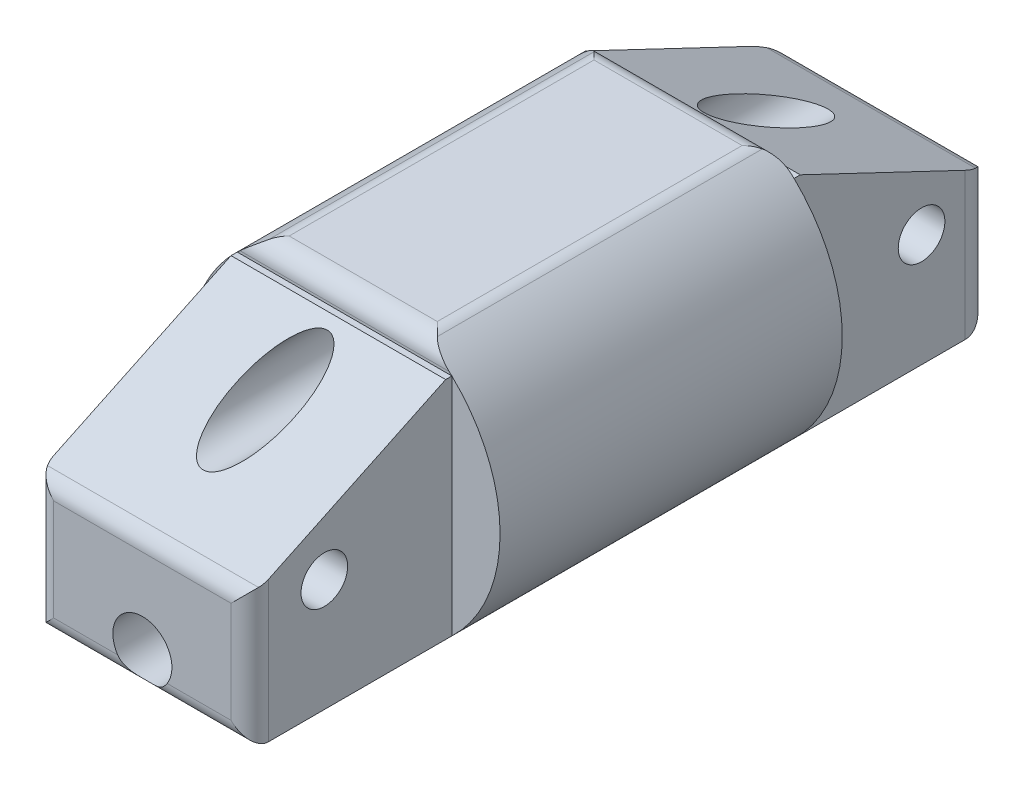
SolidWorks part; units mm, degrees
ref_plane "Front Plane" through (0, 0, 0) normal (0, 0, 1) x (1, 0, 0)
ref_plane "Top Plane" through (0, 0, 0) normal (0, 1, 0) x (1, 0, 0)
ref_plane "Right Plane" through (0, 0, 0) normal (1, 0, 0) x (0, 0, -1)
sketch "Sketch1" plane through (0, 0, 0) normal (0, 0, 1) x (1, 0, 0)
  line L0 (0, 12.7) -> (0, -12.7) construction
  line L1 (-12.7, 0) -> (12.7, 0) construction
  circle A1 centre (0, 0) radius 12.7
  dimension "D1" = 25.4
extrude "FingerBody" add sketch "Sketch1" along normal blind 27.94
ref_plane "MiddleSection" through (0, 0, 13.97) normal (0, 0, -1) x (-1, 0, 0)
ref_plane "CirclePlane" through (0, 0, 0) normal (-1, 0, 0) x (0, -1, 0)
ref_plane "CirclePlane2" through (0, 0, 0) normal (0, -1, 0) x (1, 0, 0)
sketch "Sketch2" plane through (0, 0, 0) normal (0, 0, -1) x (-1, 0, 0)
  line L0 (8.763, -9.1924) -> (-8.763, -9.1924)
  line L2 (12.7, 0) -> (-12.7, 0) construction
  line L3 (8.763, 9.1924) -> (-8.763, 9.1924)
  line L4 (8.763, -9.1924) -> (8.763, 9.1924)
  line L5 (-8.763, -9.1924) -> (-8.763, 9.1924)
  circle A1 centre (0, 0) radius 12.7 construction
  dimension "D1" = 17.526
  dimension "D2" = 17.526
extrude "Boss-Extrude2" add sketch "Sketch2" along normal blind 16.51
mirror "Mirror1" about plane through (0, 0, 13.97) normal (0, 0, -1) of "Boss-Extrude2"
sketch "Sketch3" plane through (0, 0, 44.45) normal (0, 0, 1) x (1, 0, 0)
  line L0 (0, 9.1924) -> (0, -9.1924) construction
  line L1 (-8.763, 9.1924) -> (8.763, 9.1924) construction
  line L2 (8.763, -9.1924) -> (-8.763, -9.1924) construction
  circle A0 centre (0, 0) radius 6.5251
sketch "Sketch4" plane through (-8.763, 0, 0) normal (-1, 0, 0) x (0, 0, 1)
  line L0 (38.354, -9.1924) -> (38.354, 9.1924) construction
  line L3 (44.45, -9.1924) -> (27.94, -9.1924) construction
  line L6 (44.45, 9.1924) -> (27.94, 9.1924) construction
  line L7 (27.94, 0) -> (38.354, 0) construction
  line L8 (27.94, -9.1924) -> (27.94, 9.1924) construction
  circle A0 centre (38.354, 0) radius 1.905
  dimension "D1" = 10.414
extrude "Cut-Extrude2" cut sketch "Sketch4" against normal through all
mirror "Mirror2" about plane through (0, 0, 13.97) normal (0, 0, -1) of "Cut-Extrude2"
sketch "Sketch5" plane through (8.763, 0, 0) normal (1, 0, 0) x (0, 0, -1)
  line L0 (16.51, 1.5724) -> (0.508, 9.1924)
  line L1 (16.51, 9.1924) -> (16.51, -9.1924) construction
  line L2 (16.51, 9.1924) -> (0, 9.1924) construction
  line L3 (0.508, 9.1924) -> (16.51, 9.1924)
  line L4 (16.51, 9.1924) -> (16.51, 1.5724)
  dimension "D1" = 7.62
  dimension "D2" = 16.002
extrude "Cut-Extrude3" cut sketch "Sketch5" against normal through all
fillet "Fillet2" radius 2.54 4 edges at (0, -9.1924, -16.51) (8.763, -3.81, -16.51) (-8.763, -3.81, -16.51) (0, 1.5724, -16.51)
mirror "Mirror6" about plane through (0, 0, 13.97) normal (0, 0, -1) of "Cut-Extrude3"
sketch "Sketch8" plane through (0, 0, 0) normal (0, 0, -1) x (-1, 0, 0)
  line L0 (6.4807, 10.922) -> (-6.4807, 10.922)
  line L1 (12.7, 0) -> (-12.7, 0) construction
  circle A0 centre (0, 0) radius 12.7 construction
  arc A1 (6.4807, 10.922) -> (-6.4807, 10.922) centre (0, 0) ccw
  point P2 (0, 10.922)
  dimension "D1" = 10.922
extrude "Cut-Extrude5" cut sketch "Sketch8" against normal through all both and the other way through all
mirror "Mirror7" about plane through (0, 0, 0) normal (0, -1, 0) of "Cut-Extrude5"
fillet "Fillet3" radius 1.524 4 edges at (6.4807, 10.922, 13.97) (-6.4807, 10.922, 13.97) (0, 10.922, 0) (0, 10.922, 27.94)
fillet "Fillet4" radius 1.524 4 edges at (0, -10.922, 27.94) (-6.4807, -10.922, 13.97) (6.4807, -10.922, 13.97) (0, -10.922, 0)
fillet "Fillet6" radius 1.524 4 edges at (0, -9.1924, 44.45) (-8.763, -3.81, 44.45) (0, 1.5724, 44.45) (8.763, -3.81, 44.45)
sketch "Sketch11" plane through (0, 0, 27.94) normal (0, 0, 1) x (1, 0, 0)
  line L0 (0, 0) -> (-12.7, 0) construction
  line L1 (0, 0) -> (0, -12.7) construction
  line L2 (0, 0) -> (0, 12.6488) construction
  circle A0 centre (0, 0) radius 12.7 construction
  circle A1 centre (0, 6.35) radius 2.413
  circle A2 centre (0, -6.35) radius 2.413
  dimension "D1" = 6.35
  dimension "D2" = 6.35
extrude "Cut-Extrude6" cut sketch "Sketch11" against normal through all and the other way through all
